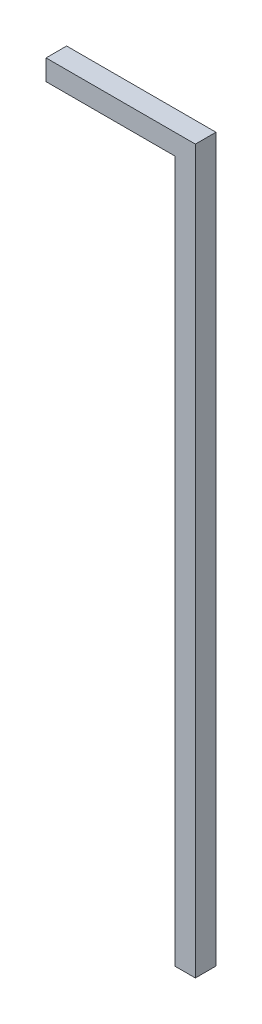
SolidWorks part; units mm, degrees
ref_plane "Front Plane" through (0, 0, 0) normal (0, 0, 1) x (1, 0, 0)
ref_plane "Top Plane" through (0, 0, 0) normal (0, 1, 0) x (1, 0, 0)
ref_plane "Right Plane" through (0, 0, 0) normal (1, 0, 0) x (0, 0, -1)
sketch "Sketch1" plane through (0, 0, 0) normal (0, 0, 1) x (1, 0, 0)
  line L0 (259.0449, 201.4917) -> (404.0449, 201.4917)
  line L1 (404.0449, 201.4917) -> (404.0449, -499.8383)
  line L2 (404.0449, -499.8383) -> (384.0449, -499.8383)
  line L3 (384.0449, -499.8383) -> (384.0449, 181.4917)
  line L4 (384.0449, 181.4917) -> (259.0449, 181.4917)
  line L5 (259.0449, 181.4917) -> (259.0449, 201.4917)
  dimension "D1" = 701.33
  dimension "D2" = 145
  dimension "D3" = 20
  dimension "D4" = 20
extrude "Boss-Extrude1" add sketch "Sketch1" along normal blind 20
